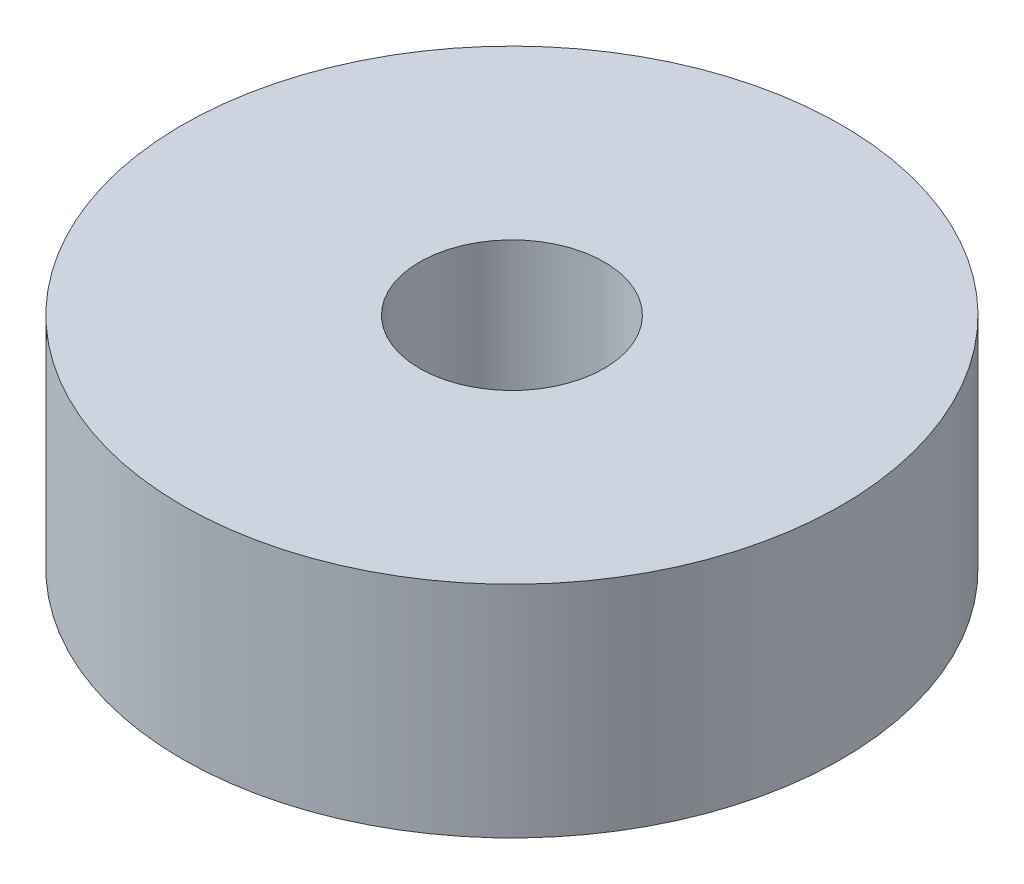
SolidWorks part; units mm, degrees
ref_plane "前视基准面" through (0, 0, 0) normal (0, 0, 1) x (1, 0, 0)
ref_plane "上视基准面" through (0, 0, 0) normal (0, 1, 0) x (1, 0, 0)
ref_plane "右视基准面" through (0, 0, 0) normal (1, 0, 0) x (0, 0, -1)
other "Configuration Table"
sketch "草图1" plane through (0, 0, 0) normal (0, 1, 0) x (1, 0, 0)
  circle A0 centre (0, 0) radius 7.5
  circle A1 centre (0, 0) radius 2.1
  dimension "D1" = 15
  dimension "D2" = 4.2
extrude "凸台-拉伸1" add sketch "草图1" along normal blind 5
